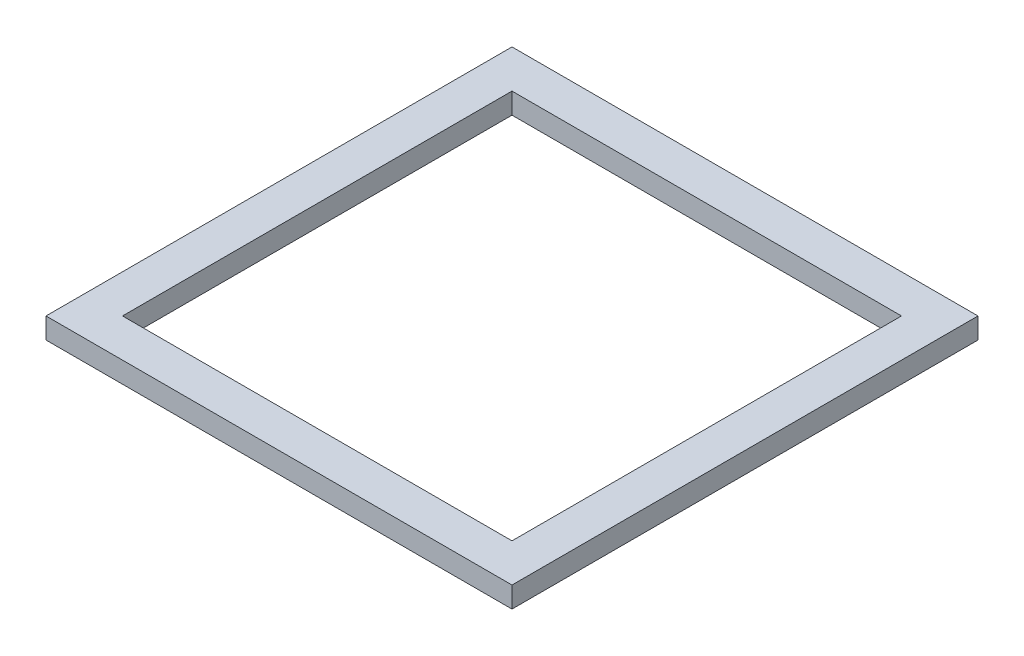
SolidWorks part; units mm, degrees
ref_plane "Front Plane" through (0, 0, 0) normal (0, 0, 1) x (1, 0, 0)
ref_plane "Top Plane" through (0, 0, 0) normal (0, 1, 0) x (1, 0, 0)
ref_plane "Right Plane" through (0, 0, 0) normal (1, 0, 0) x (0, 0, -1)
sketch "Sketch1" plane through (0, 0, 0) normal (0, 1, 0) x (1, 0, 0)
  line L1 (-200.0795, -359.6837) -> (155.5205, -359.6837)
  line L2 (-200.0795, -359.6837) -> (-200.0795, -715.2837)
  line L3 (-200.0795, -715.2837) -> (155.5205, -715.2837)
  line L4 (155.5205, -359.6837) -> (155.5205, -715.2837)
  line L5 (-235.0045, -324.7587) -> (190.4455, -324.7587)
  line L6 (-235.0045, -324.7587) -> (-235.0045, -750.2087)
  line L7 (-235.0045, -750.2087) -> (190.4455, -750.2087)
  line L8 (190.4455, -324.7587) -> (190.4455, -750.2087)
  line L9 (-22.2795, -324.7587) -> (-22.2795, -359.6837) construction
  line L10 (-22.2795, -359.6837) -> (-22.2795, -534.3506) construction
  line L11 (-22.2795, -534.3506) -> (-200.0795, -534.3506) construction
  line L12 (-200.0795, -534.3506) -> (-235.0045, -534.3506) construction
  line L13 (-22.2795, -715.2837) -> (-22.2795, -750.2087) construction
  line L14 (-22.2795, -750.2087) -> (155.5205, -563.2664) construction
  line L15 (155.5205, -563.2664) -> (190.4455, -563.2664) construction
  dimension "D1" = 425.45
  dimension "D2" = 425.45
  dimension "D3" = 355.6
extrude "Boss-Extrude1" add sketch "Sketch1" along normal blind 19.05
